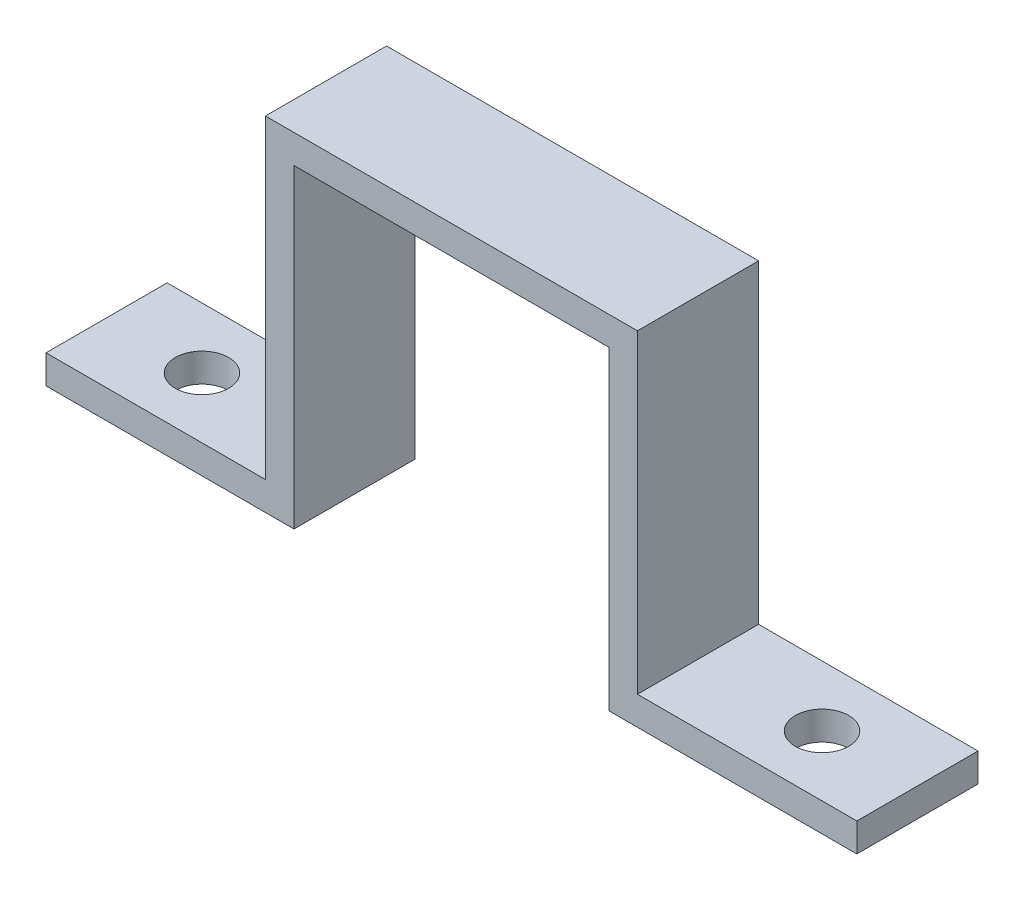
SolidWorks part; units mm, degrees
ref_plane "Front Plane" through (0, 0, 0) normal (0, 0, 1) x (1, 0, 0)
ref_plane "Top Plane" through (0, 0, 0) normal (0, 1, 0) x (1, 0, 0)
ref_plane "Right Plane" through (0, 0, 0) normal (1, 0, 0) x (0, 0, -1)
sketch "Sketch1" plane through (0, 0, 0) normal (0, 0, 1) x (1, 0, 0)
  line L0 (-42.5, 0) -> (-16.5, 0)
  line L1 (-16.5, 0) -> (-16.5, 33)
  line L2 (-16.5, 33) -> (16.5, 33)
  line L3 (0, 33) -> (0, 0) construction
  line L4 (16.5, 0) -> (16.5, 33)
  line L5 (42.5, 0) -> (16.5, 0)
  dimension "D1" = 33
  dimension "D2" = 33
  dimension "D3" = 85
extrude "Extrude-Thin1" add sketch "Sketch1" along normal blind 6.35 and the other way blind 6.35 thin thin type one direction wall 3
sketch "Sketch2" plane through (0, 0, 0) normal (0, 1, 0) x (1, 0, 0)
  line L0 (-32.5, 0) -> (0, 0) construction
  line L1 (0, -6.6) -> (0, 6.6) construction
  circle A0 centre (-32.5, 0) radius 2.8
  circle A1 centre (32.5, 0) radius 2.8
  dimension "D1" = 5.6
  dimension "D2" = 32.5
extrude "Cut-Extrude2" cut sketch "Sketch2" against normal through all and the other way through all contours A1 | A0
